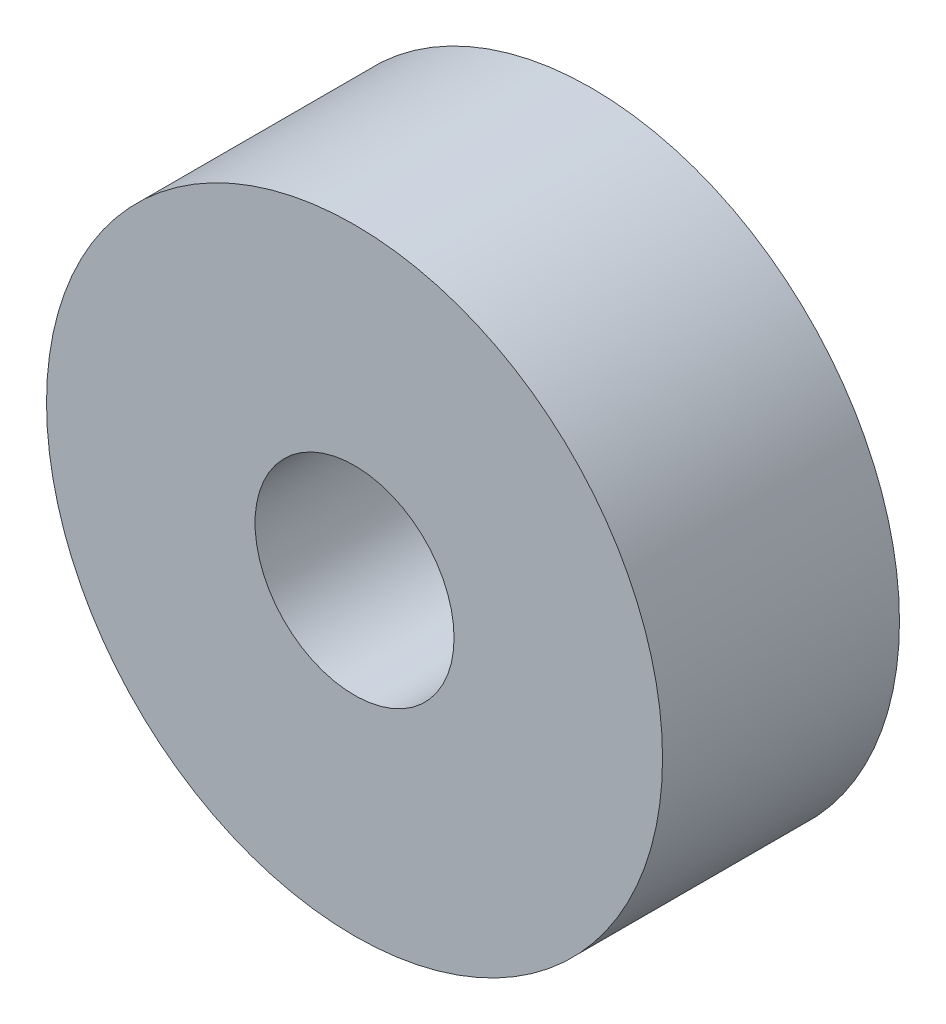
SolidWorks part; units mm, degrees
material "ABS"
ref_plane "前视基准面" through (0, 0, 0) normal (0, 0, 1) x (1, 0, 0)
ref_plane "上视基准面" through (0, 0, 0) normal (0, 1, 0) x (1, 0, 0)
ref_plane "右视基准面" through (0, 0, 0) normal (1, 0, 0) x (0, 0, -1)
sketch "草图1" plane through (0, 0, 0) normal (0, 0, 1) x (1, 0, 0)
  circle A0 centre (0, 0) radius 6.5
  circle A1 centre (0, 0) radius 2.1
  dimension "D1" = 4.2
  dimension "D2" = 13
extrude "凸台-拉伸1" add sketch "草图1" along normal blind 5
